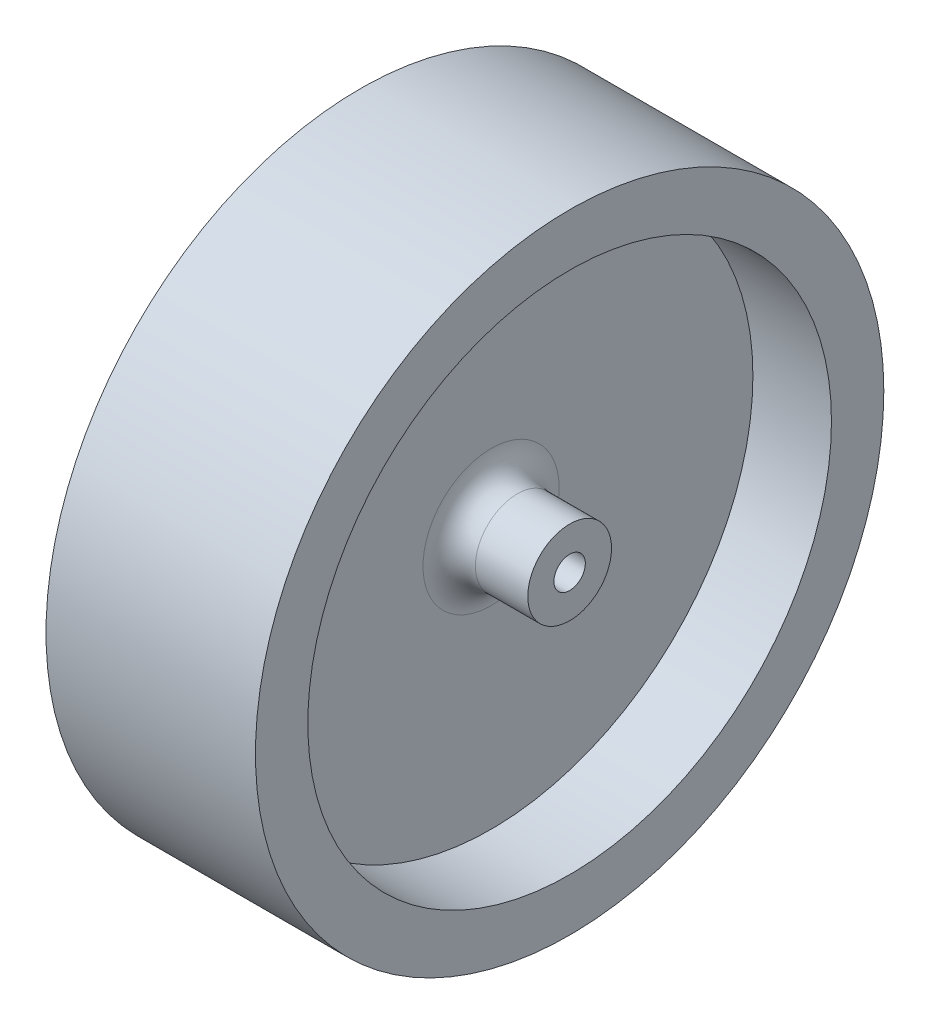
SolidWorks part; units mm, degrees
material "HYPALON"
ref_plane "Front Plane" through (0, 0, 0) normal (0, 0, 1) x (1, 0, 0)
ref_plane "Top Plane" through (0, 0, 0) normal (0, 1, 0) x (1, 0, 0)
ref_plane "Right Plane" through (0, 0, 0) normal (1, 0, 0) x (0, 0, -1)
sketch "Sketch2" plane through (0, 0, 0) normal (1, 0, 0) x (0, 0, -1)
  circle A0 centre (0, 0) radius 60
extrude "Boss-Extrude1" add sketch "Sketch2" along normal blind 40
sketch "Sketch3" plane through (40, 0, 0) normal (1, 0, 0) x (0, 0, -1)
  circle A0 centre (0, 0) radius 50
extrude "Cut-Extrude1" cut sketch "Sketch3" against normal blind 15
sketch "Sketch4" plane through (0, 0, 0) normal (-1, 0, 0) x (0, 0, 1)
  circle A0 centre (0, 0) radius 50
extrude "Cut-Extrude2" cut sketch "Sketch4" against normal blind 15
sketch "Sketch5" plane through (15, 0, 0) normal (-1, 0, 0) x (0, 0, 1)
  circle A0 centre (0, 0) radius 8
extrude "Boss-Extrude2" add sketch "Sketch5" along normal blind 15
sketch "Sketch6" plane through (25, 0, 0) normal (1, 0, 0) x (0, 0, -1)
  circle A0 centre (0, 0) radius 8
extrude "Boss-Extrude3" add sketch "Sketch6" along normal blind 15
sketch "Sketch7" plane through (40, 0, 0) normal (1, 0, 0) x (0, 0, -1)
  circle A0 centre (0, 0) radius 3
extrude "Cut-Extrude3" cut sketch "Sketch7" against normal blind 40
fillet "Fillet2" radius 5 2 edges at (25, 0, -8) (15, 0, 8)
